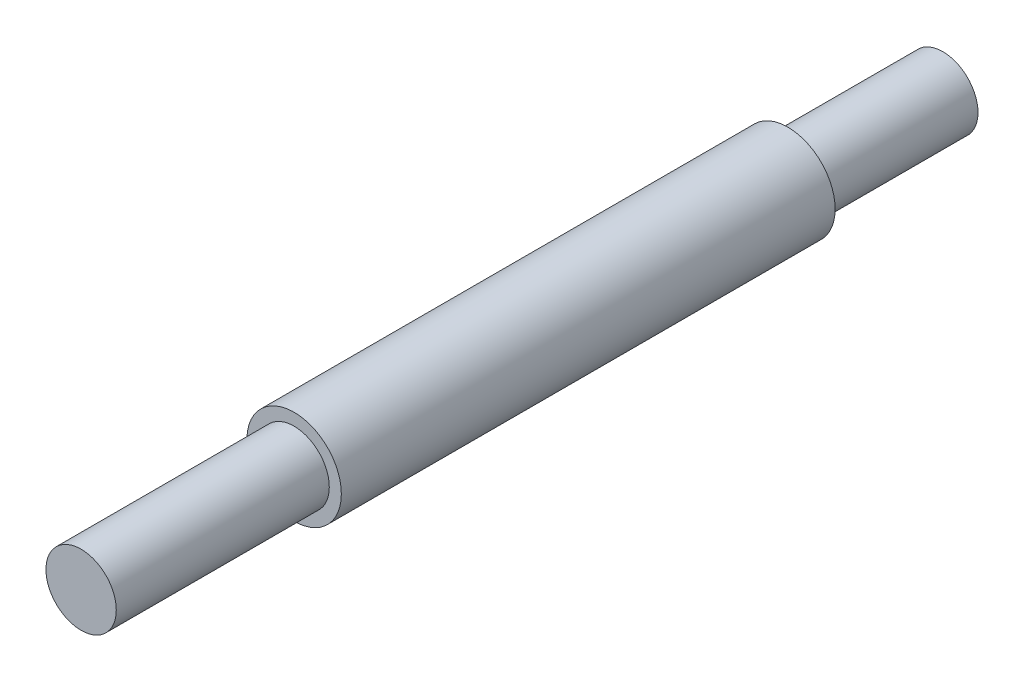
SolidWorks part; units mm, degrees
ref_plane "Front Plane" through (0, 0, 0) normal (0, 0, 1) x (1, 0, 0)
ref_plane "Top Plane" through (0, 0, 0) normal (0, 1, 0) x (1, 0, 0)
ref_plane "Right Plane" through (0, 0, 0) normal (1, 0, 0) x (0, 0, -1)
sketch "Sketch1" plane through (0, 0, 0) normal (0, 0, 1) x (1, 0, 0)
  circle A0 centre (0, 0) radius 2.4384
  circle A1 centre (0, 0) radius 1.397
  dimension "D1" = 4.8768
  dimension "D2" = 2.794
extrude "Boss-Extrude1" add sketch "Sketch1" along normal blind 25.4991
sketch "Croquis1" plane through (0, 0, 25.4991) normal (0, 0, 1) x (1, 0, 0)
  circle A0 centre (0, 0) radius 1.8161
  dimension "D1" = 3.6322
extrude "Saliente-Extruir1" add sketch "Croquis1" along normal blind 11
sketch "Croquis2" plane through (0, 0, 0) normal (0, 0, -1) x (-1, 0, 0)
  circle A0 centre (0, 0) radius 1.8161
  dimension "D1" = 3.6322
extrude "Saliente-Extruir2" add sketch "Croquis2" along normal mid plane 16
